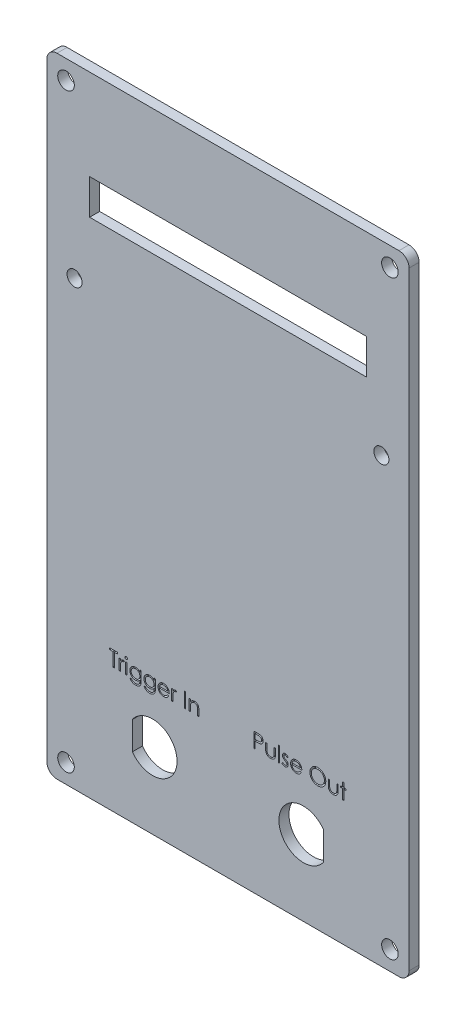
SolidWorks part; units mm, degrees
ref_plane "Front Plane" through (0, 0, 0) normal (0, 0, 1) x (1, 0, 0)
ref_plane "Top Plane" through (0, 0, 0) normal (0, 1, 0) x (1, 0, 0)
ref_plane "Right Plane" through (0, 0, 0) normal (1, 0, 0) x (0, 0, -1)
sketch "Sketch1" plane through (0, 0, 0) normal (0, 0, 1) x (1, 0, 0)
  line L5 (-36, 50) -> (36, 50)
  line L6 (-36, 50) -> (-36, -75)
  line L7 (-36, -75) -> (36, -75)
  line L8 (36, 50) -> (36, -75)
  dimension "D1" = 72
  dimension "D2" = 36
  dimension "D3" = 125
  dimension "D4" = 75
extrude "Boss-Extrude1" add sketch "Sketch1" along normal blind 2
fillet "Fillet3" radius 2 4 edges at (-36, 50, 1) (36, 50, 1) (-36, -75, 1) (36, -75, 1)
sketch "Sketch2" plane through (0, 0, 2) normal (0, 0, 1) x (1, 0, 0)
  line L0 (34, 50) -> (-34, 50) construction
  line L1 (-36, 48) -> (-36, -73) construction
  circle A0 centre (-32.2, 46.2) radius 1.65
  dimension "D1" = 3.3
  dimension "D2" = 3.8
  dimension "D3" = 3.8
extrude "Cut-Extrude1" cut sketch "Sketch2" against normal through all
mirror "Mirror1" about plane through (0, 0, 0) normal (1, 0, 0) of "Cut-Extrude1"
mirror "Mirror2" [suppressed] about plane through (0, 0, 0) normal (0, 1, 0)
sketch "Sketch3" plane through (0, 0, 2) normal (0, 0, 1) x (1, 0, 0)
  line L5 (-27.5, 32) -> (27.5, 32)
  line L6 (-27.5, 32) -> (-27.5, 25)
  line L7 (-27.5, 25) -> (27.5, 25)
  line L8 (27.5, 32) -> (27.5, 25)
  dimension "D1" = 55
  dimension "D2" = 7
  dimension "D3" = 25
  dimension "D4" = 27.5
extrude "Cut-Extrude2" cut sketch "Sketch3" against normal through all
sketch "Sketch4" plane through (0, 0, 2) normal (0, 0, 1) x (1, 0, 0)
  circle A0 centre (-15, -60) radius 4.875
  dimension "D1" = 9.75
  dimension "D2" = 60
  dimension "D3" = 15
extrude "Cut-Extrude3" cut sketch "Sketch4" against normal blind 10
mirror "Mirror3" about plane through (0, 0, 0) normal (1, 0, 0) of "Cut-Extrude3"
sketch "Sketch5" plane through (0, 0, 2) normal (0, 0, 1) x (1, 0, 0)
  text T0 "Trigger In" font "Century Gothic" height 3
  text T1 "Pulse Out" font "Century Gothic" height 3
extrude "Cut-Extrude4" cut sketch "Sketch5" against normal through all
sketch "Sketch6" plane through (0, 0, 2) normal (0, 0, 1) x (1, 0, 0)
  line L1 (-21.2674, -55) -> (-19, -55)
  line L2 (-21.2674, -55) -> (-21.2674, -65)
  line L3 (-21.2674, -65) -> (-19, -65)
  line L4 (-19, -55) -> (-19, -65)
  circle A0 centre (-15, -60) radius 4.875 construction
  dimension "D1" = 4
  dimension "D2" = 10
  dimension "D3" = 5
extrude "Boss-Extrude2" add sketch "Sketch6" against normal up to surface (2 mm away) up to face at (-18.0958, -49.5596, 0)
mirror "Mirror4" about plane through (0, 0, 0) normal (1, 0, 0) of "Boss-Extrude2"
sketch "Sketch7" plane through (0, 0, 2) normal (0, 0, 1) x (1, 0, 0)
  line L0 (-36, 48) -> (-36, -73) construction
  line L1 (-34, -75) -> (34, -75) construction
  circle A0 centre (-32.2, -71.2) radius 1.65
  dimension "D1" = 3.3
  dimension "D2" = 3.8
  dimension "D3" = 3.8
extrude "Cut-Extrude5" cut sketch "Sketch7" against normal blind 10
mirror "Mirror5" about plane through (0, 0, 0) normal (1, 0, 0) of "Cut-Extrude5"
sketch "Sketch8" plane through (0, 0, 2) normal (0, 0, 1) x (1, 0, 0)
  line L0 (-27.5, 25) -> (27.5, 25) construction
  circle A0 centre (-30.5, 13) radius 1.5
  circle A1 centre (30.5, 13) radius 1.5
  dimension "D1" = 3
  dimension "D2" = 3
  dimension "D3" = 61
  dimension "D4" = 30.5
  dimension "D5" = 12
  dimension "D6" = 12
extrude "Cut-Extrude6" cut sketch "Sketch8" against normal through all
equation "\"D2@Sketch1\"=\"D1@Sketch1\"/2"
equation "\"D3@Sketch2\"=\"D2@Sketch2\""
equation "\"D3@Sketch7\"=\"D2@Sketch7\""
equation "\"D4@Sketch3\"=\"D1@Sketch3\"/2"
equation "\"D4@Sketch8\"=\"D3@Sketch8\"/2"
